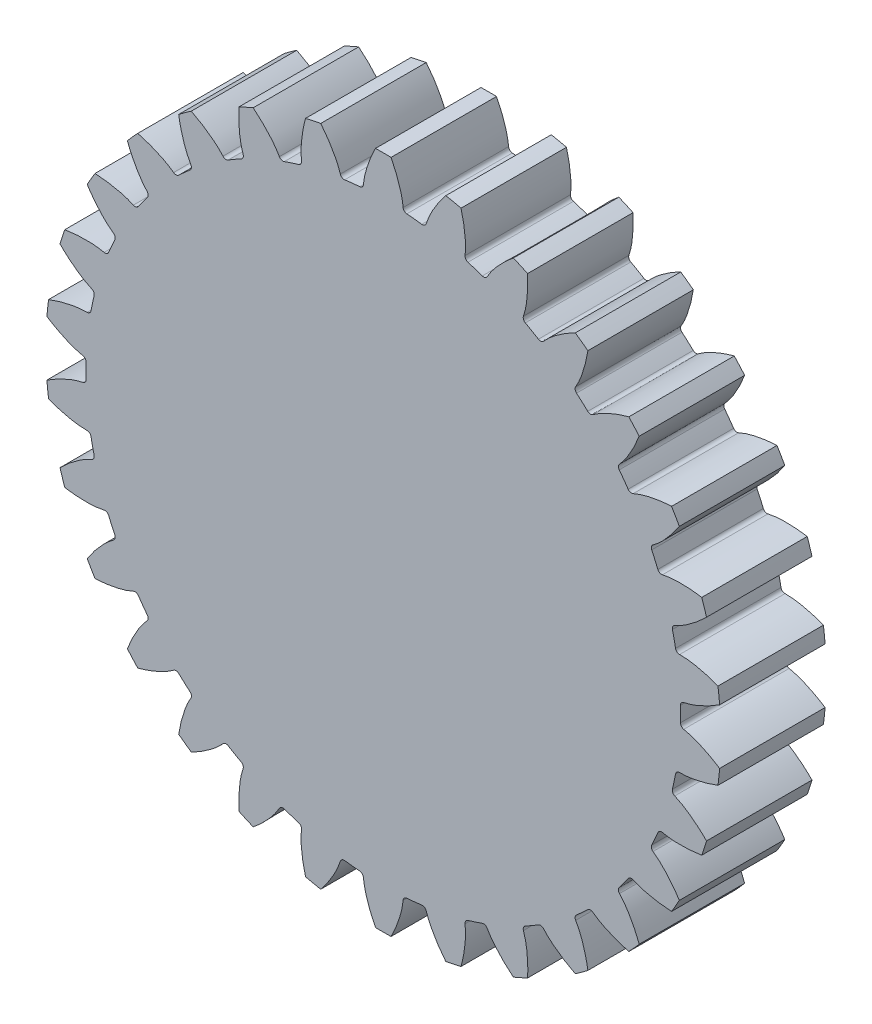
SolidWorks part; units mm, degrees
ref_plane "前视基准面" through (0, 0, 0) normal (0, 0, 1) x (1, 0, 0)
ref_plane "上视基准面" through (0, 0, 0) normal (0, 1, 0) x (1, 0, 0)
ref_plane "右视基准面" through (0, 0, 0) normal (1, 0, 0) x (0, 0, -1)
other "Configuration Table"
sketch "circles" plane through (0, 0, 0) normal (0, 0, 1) x (1, 0, 0)
  circle A0 centre (0, 0) radius 32
  circle A1 centre (0, 0) radius 27.5
  circle A2 centre (0, 0) radius 28.1908
  circle A3 centre (0, 0) radius 30
  dimension "D1" = 60
  dimension "D2" = 56.3816
  dimension "D3" = 55
  dimension "D4" = 64
extrude "Gear_extrude" add sketch "circles" along normal blind 10 contours A0
sketch "Involute" plane through (0, 0, 10) normal (0, 0, 1) x (1, 0, 0)
  spline S0 degree 4 poles (28.171, -1.0557) (28.2223, -1.0593) (28.3658, -1.0748) (28.6344, -1.1247) (29.0665, -1.2353) (29.6059, -1.4183) (30.2862, -1.7021) (31.0629, -2.0956) (31.8862, -2.5882) (32.9602, -3.3359) (34.1728, -4.337) (35.451, -5.5998) (36.7769, -7.1739) (37.9681, -8.8517) (39.0285, -10.6149) (39.9764, -12.4839) (40.7958, -14.4124) (41.4038, -16.142) (41.8493, -17.6484) (42.1713, -18.9171) (42.3998, -19.9389) (42.6495, -21.2237) (42.8522, -22.517) (43.0089, -23.8165) (43.1207, -25.1207) (43.1836, -26.1655) (43.2157, -27.0819) (43.2272, -27.8657) (43.226, -28.5232) (43.2194, -29.0333) (43.2013, -29.7091) (43.1793, -30.2472) (43.1275, -31.2203) (43.075, -31.832) (43.0114, -32.5795) (42.9682, -32.9515) (42.9431, -33.1951) (42.9309, -33.297) knots 0 0 0 0 0 0.005377 0.015084 0.028532 0.04661 0.064855 0.092111 0.119476 0.146842 0.201575 0.256307 0.307035 0.361767 0.4165 0.471232 0.525964 0.580697 0.608063 0.635429 0.662795 0.690161 0.744894 0.77226 0.799626 0.826992 0.854358 0.868042 0.881725 0.895408 0.909091 0.931818 0.954545 0.977273 0.988636 1 1 1 1 1 construction
  spline S2 degree 4 poles (28.171, 1.0557) (28.2223, 1.0593) (28.3658, 1.0748) (28.6344, 1.1247) (29.0665, 1.2353) (29.6059, 1.4183) (30.2862, 1.7021) (31.0629, 2.0956) (31.8862, 2.5882) (32.9602, 3.3359) (34.1728, 4.337) (35.451, 5.5998) (36.7769, 7.1739) (37.9681, 8.8517) (39.0285, 10.6149) (39.9764, 12.4839) (40.7958, 14.4124) (41.4038, 16.142) (41.8493, 17.6484) (42.1713, 18.9171) (42.3998, 19.9389) (42.6495, 21.2237) (42.8522, 22.517) (43.0089, 23.8165) (43.1207, 25.1207) (43.1836, 26.1655) (43.2157, 27.0819) (43.2272, 27.8657) (43.226, 28.5232) (43.2194, 29.0333) (43.2013, 29.7091) (43.1793, 30.2472) (43.1275, 31.2203) (43.075, 31.832) (43.0114, 32.5795) (42.9682, 32.9515) (42.9431, 33.1951) (42.9309, 33.297) knots 0 0 0 0 0 0.005377 0.015084 0.028532 0.04661 0.064855 0.092111 0.119476 0.146842 0.201575 0.256307 0.307035 0.361767 0.4165 0.471232 0.525964 0.580697 0.608063 0.635429 0.662795 0.690161 0.744894 0.77226 0.799626 0.826992 0.854358 0.868042 0.881725 0.895408 0.909091 0.931818 0.954545 0.977273 0.988636 1 1 1 1 1 construction
  spline S3 degree 4 poles (28.171, 1.0557) (28.2223, 1.0593) (28.3658, 1.0748) (28.6344, 1.1247) (29.0665, 1.2353) (29.6059, 1.4183) (30.2862, 1.7021) (31.0629, 2.0956) (31.8862, 2.5882) (32.9602, 3.3359) (34.1728, 4.337) (35.451, 5.5998) (36.7769, 7.1739) (37.9681, 8.8517) (39.0285, 10.6149) (39.9764, 12.4839) (40.7958, 14.4124) (41.4038, 16.142) (41.8493, 17.6484) (42.1713, 18.9171) (42.3998, 19.9389) (42.6495, 21.2237) (42.8522, 22.517) (43.0089, 23.8165) (43.1207, 25.1207) (43.1836, 26.1655) (43.2157, 27.0819) (43.2272, 27.8657) (43.226, 28.5232) (43.2194, 29.0333) (43.2078, 29.4683) (43.1997, 29.7103) (43.1953, 29.8292) knots 0 0 0 0 0 0.005377 0.015084 0.028532 0.04661 0.064855 0.092111 0.119476 0.146842 0.201575 0.256307 0.307035 0.361767 0.4165 0.471232 0.525964 0.580697 0.608063 0.635429 0.662795 0.690161 0.744894 0.77226 0.799626 0.826992 0.854358 0.868042 0.881725 0.895408 0.909091 0.909091 0.909091 0.909091 0.909091
  spline S4 degree 4 poles (28.171, -1.0557) (28.2223, -1.0593) (28.3658, -1.0748) (28.6344, -1.1247) (29.0665, -1.2353) (29.6059, -1.4183) (30.2862, -1.7021) (31.0629, -2.0956) (31.8862, -2.5882) (32.9602, -3.3359) (34.1728, -4.337) (35.451, -5.5998) (36.7769, -7.1739) (37.9681, -8.8517) (39.0285, -10.6149) (39.9764, -12.4839) (40.7958, -14.4124) (41.4038, -16.142) (41.8493, -17.6484) (42.1713, -18.9171) (42.3998, -19.9389) (42.6495, -21.2237) (42.8522, -22.517) (43.0089, -23.8165) (43.1207, -25.1207) (43.1836, -26.1655) (43.2157, -27.0819) (43.2272, -27.8657) (43.226, -28.5232) (43.2194, -29.0333) (43.2078, -29.4683) (43.1997, -29.7103) (43.1953, -29.8292) knots 0 0 0 0 0 0.005377 0.015084 0.028532 0.04661 0.064855 0.092111 0.119476 0.146842 0.201575 0.256307 0.307035 0.361767 0.4165 0.471232 0.525964 0.580697 0.608063 0.635429 0.662795 0.690161 0.744894 0.77226 0.799626 0.826992 0.854358 0.868042 0.881725 0.895408 0.909091 0.909091 0.909091 0.909091 0.909091
sketch "Db>Df" plane through (0, 0, 10) normal (0, 0, 1) x (1, 0, 0)
  line L2 (0, 0) -> (29.9589, 1.5701) construction
  line L3 (0, 0) -> (60.2478, -1.5776) construction
  line L4 (43.1953, 29.8292) -> (60.2478, -1.5776)
  line L5 (60.2478, -1.5776) -> (43.1953, -29.8292)
  circle A2 centre (0, 0) radius 30 construction
  circle A3 centre (0, 0) radius 28.1908 construction
  arc A4 (28.171, -1.0557) -> (28.171, 1.0557) centre (0, 0) ccw
  spline S0 degree 4 poles (-58.7454, -1999.1168) (17.076, -52.2104) (22.5891, -1.8433) (25.9954, -0.4491) (29.0665, -1.2353) (29.6059, -1.4183) (30.2862, -1.7021) (31.0629, -2.0956) (31.8862, -2.5882) (32.9602, -3.3359) (34.1728, -4.337) (35.451, -5.5998) (36.7769, -7.1739) (37.9681, -8.8517) (39.0285, -10.6149) (39.9764, -12.4839) (40.7958, -14.4124) (41.4038, -16.142) (41.8493, -17.6484) (42.1713, -18.9171) (42.3998, -19.9389) (42.6495, -21.2237) (42.8522, -22.517) (43.0089, -23.8165) (43.1207, -25.1207) (43.1836, -26.1655) (43.2157, -27.0819) (43.2272, -27.8657) (43.226, -28.5232) (43.1903, -31.2711) (42.8434, -36.3545) (44.7406, 23.1759) (-32.5965, -2028.0551) knots -0.284666 -0.284666 -0.284666 -0.284666 -0.284666 0.005377 0.015084 0.028532 0.04661 0.064855 0.092111 0.119476 0.146842 0.201575 0.256307 0.307035 0.361767 0.4165 0.471232 0.525964 0.580697 0.608063 0.635429 0.662795 0.690161 0.744894 0.77226 0.799626 0.826992 0.854358 0.868042 0.881725 0.895408 1.149228 1.149228 1.149228 1.149228 1.149228 only from (28.171, -1.0557) to (43.1953, -29.8292) construction
  spline S1 degree 4 poles (-58.7454, 1999.1168) (17.076, 52.2104) (22.5891, 1.8433) (25.9954, 0.4491) (29.0665, 1.2353) (29.6059, 1.4183) (30.2862, 1.7021) (31.0629, 2.0956) (31.8862, 2.5882) (32.9602, 3.3359) (34.1728, 4.337) (35.451, 5.5998) (36.7769, 7.1739) (37.9681, 8.8517) (39.0285, 10.6149) (39.9764, 12.4839) (40.7958, 14.4124) (41.4038, 16.142) (41.8493, 17.6484) (42.1713, 18.9171) (42.3998, 19.9389) (42.6495, 21.2237) (42.8522, 22.517) (43.0089, 23.8165) (43.1207, 25.1207) (43.1836, 26.1655) (43.2157, 27.0819) (43.2272, 27.8657) (43.226, 28.5232) (43.1903, 31.2711) (42.8434, 36.3545) (44.7406, -23.1759) (-32.5965, 2028.0551) knots -0.284666 -0.284666 -0.284666 -0.284666 -0.284666 0.005377 0.015084 0.028532 0.04661 0.064855 0.092111 0.119476 0.146842 0.201575 0.256307 0.307035 0.361767 0.4165 0.471232 0.525964 0.580697 0.608063 0.635429 0.662795 0.690161 0.744894 0.77226 0.799626 0.826992 0.854358 0.868042 0.881725 0.895408 1.149228 1.149228 1.149228 1.149228 1.149228 only from (28.171, 1.0557) to (43.1953, 29.8292) construction
  spline S2 degree 4 poles (28.171, -1.0557) (28.2223, -1.0593) (28.3658, -1.0748) (28.6344, -1.1247) (29.0665, -1.2353) (29.6059, -1.4183) (30.2862, -1.7021) (31.0629, -2.0956) (31.8862, -2.5882) (32.9602, -3.3359) (34.1728, -4.337) (35.451, -5.5998) (36.7769, -7.1739) (37.9681, -8.8517) (39.0285, -10.6149) (39.9764, -12.4839) (40.7958, -14.4124) (41.4038, -16.142) (41.8493, -17.6484) (42.1713, -18.9171) (42.3998, -19.9389) (42.6495, -21.2237) (42.8522, -22.517) (43.0089, -23.8165) (43.1207, -25.1207) (43.1836, -26.1655) (43.2157, -27.0819) (43.2272, -27.8657) (43.226, -28.5232) (43.2194, -29.0333) (43.2078, -29.4683) (43.1997, -29.7103) (43.1953, -29.8292) knots 0 0 0 0 0 0.005377 0.015084 0.028532 0.04661 0.064855 0.092111 0.119476 0.146842 0.201575 0.256307 0.307035 0.361767 0.4165 0.471232 0.525964 0.580697 0.608063 0.635429 0.662795 0.690161 0.744894 0.77226 0.799626 0.826992 0.854358 0.868042 0.881725 0.895408 0.909091 0.909091 0.909091 0.909091 0.909091
  spline S3 degree 4 poles (28.171, 1.0557) (28.2223, 1.0593) (28.3658, 1.0748) (28.6344, 1.1247) (29.0665, 1.2353) (29.6059, 1.4183) (30.2862, 1.7021) (31.0629, 2.0956) (31.8862, 2.5882) (32.9602, 3.3359) (34.1728, 4.337) (35.451, 5.5998) (36.7769, 7.1739) (37.9681, 8.8517) (39.0285, 10.6149) (39.9764, 12.4839) (40.7958, 14.4124) (41.4038, 16.142) (41.8493, 17.6484) (42.1713, 18.9171) (42.3998, 19.9389) (42.6495, 21.2237) (42.8522, 22.517) (43.0089, 23.8165) (43.1207, 25.1207) (43.1836, 26.1655) (43.2157, 27.0819) (43.2272, 27.8657) (43.226, 28.5232) (43.2194, 29.0333) (43.2078, 29.4683) (43.1997, 29.7103) (43.1953, 29.8292) knots 0 0 0 0 0 0.005377 0.015084 0.028532 0.04661 0.064855 0.092111 0.119476 0.146842 0.201575 0.256307 0.307035 0.361767 0.4165 0.471232 0.525964 0.580697 0.608063 0.635429 0.662795 0.690161 0.744894 0.77226 0.799626 0.826992 0.854358 0.868042 0.881725 0.895408 0.909091 0.909091 0.909091 0.909091 0.909091
  dimension "D1" = 4.5
  dimension "D2" = 60
extrude "extruded-cut1" cut sketch "Db>Df" against normal through all
fillet "fillet1" radius 0.38 2 edges at (28.171, -1.0557, 5) (28.171, 1.0557, 5)
pattern_circular "circular-parttern1" count 30 over 360 about axis through (0, 0, 10) along (0, 0, -1) of "extruded-cut1", "fillet1"
sketch "Db<Df" [suppressed] plane through (0, 0, 10) normal (0, 0, 1) x (1, 0, 0)
  line L0 (0, 0) -> (100.8439, 0) construction
  line L1 (0, 0) -> (49.9753, 1.5705) construction
  line L2 (73.0175, 48.1968) -> (100.8439, 0)
  line L3 (100.8439, 0) -> (73.0175, -48.1968)
  circle A0 centre (0, 0) radius 47.5 construction
  arc A1 (47.4927, -0.8355) -> (47.4927, 0.8355) centre (0, 0) ccw
  circle A2 centre (0, 0) radius 50 construction
  spline S0 degree 4 poles (69.1798, -1998.5936) (37.8966, 59.197) (41.8514, 1.7937) (44.8419, 0.3903) (47.7946, 0.8837) (48.4767, 1.0444) (49.3818, 1.3297) (50.5254, 1.7793) (51.8333, 2.4075) (53.2224, 3.1999) (54.6746, 4.1663) (56.0658, 5.2211) (57.3956, 6.3522) (58.6648, 7.5507) (60.1325, 9.0778) (61.7919, 11.0209) (63.5752, 13.4244) (65.4038, 16.3254) (67.0485, 19.4065) (68.4812, 22.5914) (69.5546, 25.4522) (70.3495, 27.9469) (70.9303, 30.0495) (71.3467, 31.7445) (71.7156, 33.4497) (72.0375, 35.1657) (72.3133, 36.8876) (72.5435, 38.6195) (72.7289, 40.3511) (72.8524, 41.8792) (72.9313, 43.1759) (72.9787, 44.2811) (73.0067, 45.1233) (73.0226, 46.0516) (73.0565, 49.344) (72.7733, 58.0548) (73.7264, -18.7455) (39.1601, 2047.4863) knots -0.159153 -0.159153 -0.159153 -0.159153 -0.159153 0.002688 0.005377 0.015084 0.028532 0.04661 0.064855 0.092111 0.119476 0.146842 0.174209 0.201575 0.228941 0.256307 0.307035 0.361767 0.4165 0.471232 0.525964 0.580697 0.608063 0.635429 0.662795 0.690161 0.717528 0.744894 0.77226 0.799626 0.826992 0.840675 0.854358 0.868042 0.881725 0.895408 1.086914 1.086914 1.086914 1.086914 1.086914 only from (46.9782, 0.7758) to (73.0175, 48.1968) construction
  spline S1 degree 4 poles (47.4927, 0.8355) (47.602, 0.8537) (47.9217, 0.9139) (48.5186, 1.0576) (49.3818, 1.3297) (50.5254, 1.7793) (51.8333, 2.4075) (53.2224, 3.1999) (54.6746, 4.1663) (56.0658, 5.2211) (57.3956, 6.3522) (58.6648, 7.5507) (60.1325, 9.0778) (61.7919, 11.0209) (63.5752, 13.4244) (65.4038, 16.3254) (67.0485, 19.4065) (68.4812, 22.5914) (69.5546, 25.4522) (70.3495, 27.9469) (70.9303, 30.0495) (71.3467, 31.7445) (71.7156, 33.4497) (72.0375, 35.1657) (72.3133, 36.8876) (72.5435, 38.6195) (72.7289, 40.3511) (72.8524, 41.8792) (72.9313, 43.1759) (72.9787, 44.2811) (73.0067, 45.1233) (73.0226, 46.0516) (73.0306, 46.8265) (73.0255, 47.605) (73.0207, 47.9985) (73.0175, 48.1968) knots 0.008127 0.008127 0.008127 0.008127 0.008127 0.015084 0.028532 0.04661 0.064855 0.092111 0.119476 0.146842 0.174209 0.201575 0.228941 0.256307 0.307035 0.361767 0.4165 0.471232 0.525964 0.580697 0.608063 0.635429 0.662795 0.690161 0.717528 0.744894 0.77226 0.799626 0.826992 0.840675 0.854358 0.868042 0.881725 0.895408 0.909091 0.909091 0.909091 0.909091 0.909091
  spline S2 degree 4 poles (69.1798, 1998.5936) (37.8966, -59.197) (41.8514, -1.7937) (44.8419, -0.3903) (47.7946, -0.8837) (48.4767, -1.0444) (49.3818, -1.3297) (50.5254, -1.7793) (51.8333, -2.4075) (53.2224, -3.1999) (54.6746, -4.1663) (56.0658, -5.2211) (57.3956, -6.3522) (58.6648, -7.5507) (60.1325, -9.0778) (61.7919, -11.0209) (63.5752, -13.4244) (65.4038, -16.3254) (67.0485, -19.4065) (68.4812, -22.5914) (69.5546, -25.4522) (70.3495, -27.9469) (70.9303, -30.0495) (71.3467, -31.7445) (71.7156, -33.4497) (72.0375, -35.1657) (72.3133, -36.8876) (72.5435, -38.6195) (72.7289, -40.3511) (72.8524, -41.8792) (72.9313, -43.1759) (72.9787, -44.2811) (73.0067, -45.1233) (73.0226, -46.0516) (73.0565, -49.344) (72.7733, -58.0548) (73.7264, 18.7455) (39.1601, -2047.4863) knots -0.159153 -0.159153 -0.159153 -0.159153 -0.159153 0.002688 0.005377 0.015084 0.028532 0.04661 0.064855 0.092111 0.119476 0.146842 0.174209 0.201575 0.228941 0.256307 0.307035 0.361767 0.4165 0.471232 0.525964 0.580697 0.608063 0.635429 0.662795 0.690161 0.717528 0.744894 0.77226 0.799626 0.826992 0.840675 0.854358 0.868042 0.881725 0.895408 1.086914 1.086914 1.086914 1.086914 1.086914 only from (46.9782, -0.7758) to (73.0175, -48.1968) construction
  spline S3 degree 4 poles (47.4927, -0.8355) (47.602, -0.8537) (47.9217, -0.9139) (48.5186, -1.0576) (49.3818, -1.3297) (50.5254, -1.7793) (51.8333, -2.4075) (53.2224, -3.1999) (54.6746, -4.1663) (56.0658, -5.2211) (57.3956, -6.3522) (58.6648, -7.5507) (60.1325, -9.0778) (61.7919, -11.0209) (63.5752, -13.4244) (65.4038, -16.3254) (67.0485, -19.4065) (68.4812, -22.5914) (69.5546, -25.4522) (70.3495, -27.9469) (70.9303, -30.0495) (71.3467, -31.7445) (71.7156, -33.4497) (72.0375, -35.1657) (72.3133, -36.8876) (72.5435, -38.6195) (72.7289, -40.3511) (72.8524, -41.8792) (72.9313, -43.1759) (72.9787, -44.2811) (73.0067, -45.1233) (73.0226, -46.0516) (73.0306, -46.8265) (73.0255, -47.605) (73.0207, -47.9985) (73.0175, -48.1968) knots 0.008127 0.008127 0.008127 0.008127 0.008127 0.015084 0.028532 0.04661 0.064855 0.092111 0.119476 0.146842 0.174209 0.201575 0.228941 0.256307 0.307035 0.361767 0.4165 0.471232 0.525964 0.580697 0.608063 0.635429 0.662795 0.690161 0.717528 0.744894 0.77226 0.799626 0.826992 0.840675 0.854358 0.868042 0.881725 0.895408 0.909091 0.909091 0.909091 0.909091 0.909091
  dimension "D1" = 3
  dimension "D2" = 60
extrude "extruded-cut2" [suppressed] cut sketch "Db<Df" against normal through all
fillet "fillet2" [suppressed] radius 0.38
pattern_circular "circular-parttern2" [suppressed] count 30 over 360
equation "\"M\"= 2mm'模数"
equation "\"Z\"= 30'齿数"
equation "\"B\"= 10mm'齿宽"
equation "\"Alpha\"= 20\t'压力角"
equation "\"D\"= \"M\"*\"Z\"   '分度圆"
equation "\"Db\"= \"D\" * cos ( \"Alpha\" )  \t'基圆"
equation "\"Hax\"= 1'齿顶高系数"
equation "\"Cx\"= 0.25\t'顶隙系数"
equation "\"Ha\"= \"Hax\" * \"M\"\t'齿顶高"
equation "\"Hf\"= ( \"Hax\" + \"Cx\" ) * \"M\"\t'齿根高"
equation "\"Df\"= \"D\" - 2 * \"Hf\"\t\t'齿根圆"
equation "\"Da\"= \"D\" + 2 * \"Ha\"\t'齿顶圆"
equation "\"Theta\"= 360 * sqr ( ( 1 / cos ( \"Alpha\" ) ) ^ 2 - 1 ) / ( 2 * pi ) - atn ( sqr ( ( 1 / cos ( \"Alpha\" ) ) ^ 2 - 1 ) )"
equation "\"Phi\"= - ( 2 * pi * ( 90 / \"Z\" - \"Theta\" ) / 360 )"
equation "\"D1@circles\" = \"D\""
equation "\"D2@circles\" = \"Db\""
equation "\"D3@circles\" = \"Df\""
equation "\"D4@circles\" = \"Da\""
equation "\"D1@Gear_extrude\" = \"B\""
equation "\"D1@circular-parttern1\" = \"Z\""
equation "\"Db>Df\"= IIF ( \"Db\" > \"Df\" ,  unsuppressed  ,  suppressed  ) "
equation "\"extruded-cut1\"= IIF ( \"Db\" > \"Df\" ,  unsuppressed  ,  suppressed  ) "
equation "\"D1@Db<Df\"=90/\"Z\""
equation "\"D1@fillet1\" = 0.19 * \"M\""
equation "\"Db<Df\" = IIF ( \"Db\" < \"Df\" , \"unsuppressed\" , \"suppressed\" )"
equation "\"extruded-cut2\"= IIF ( \"Db\" < \"Df\" ,  unsuppressed  ,  suppressed  ) "
equation "\"D1@fillet2\" = 0.19 * \"M\""
equation "\"D1@circular-parttern2\" = \"Z\""
equation "\"circular-parttern2\"= IIF ( \"Db\" < \"Df\" ,  unsuppressed  ,  suppressed  ) "
equation "\"fillet1\"= IIF ( \"Db\" > \"Df\" ,  unsuppressed  ,  suppressed  ) "
equation "\"fillet2\"= IIF ( \"Db\" < \"Df\" ,  unsuppressed  ,  suppressed  ) "
equation "\"circular-parttern1\"= IIF ( \"Db\" > \"Df\" , \"unsuppressed\" , \"suppressed\" )"
